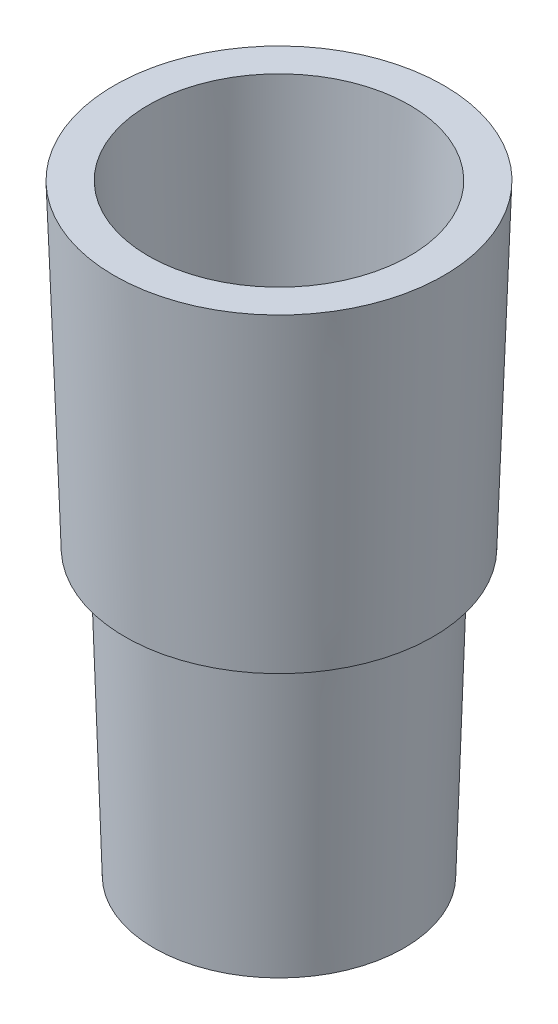
SolidWorks part; units mm, degrees
ref_plane "Front Plane" through (0, 0, 0) normal (0, 0, 1) x (1, 0, 0)
ref_plane "Top Plane" through (0, 0, 0) normal (0, 1, 0) x (1, 0, 0)
ref_plane "Right Plane" through (0, 0, 0) normal (1, 0, 0) x (0, 0, -1)
sketch "Sketch1" plane through (0, 0, 0) normal (0, 0, 1) x (1, 0, 0)
  line L0 (8, 0) -> (8, 28)
  line L2 (10.75, 30.75) -> (11.5, 53)
  line L3 (11.5, 53) -> (14.5, 53)
  line L4 (14.5, 53) -> (13.5562, 25)
  line L5 (13.5562, 25) -> (11.75, 25)
  line L6 (11.75, 25) -> (11, 0)
  line L7 (11, 0) -> (8, 0)
  line L8 (0, 0) -> (0, 41.4703) construction
  line L9 (8, 28) -> (10.75, 30.75)
  point P3 (11, 30.5112)
  dimension "D1" = 3
  dimension "D2" = 22
  dimension "D3" = 23.5
  dimension "D4" = 25
  dimension "D5" = 135
  dimension "D6" = 23
  dimension "D7" = 3
  dimension "D8" = 21.5
  dimension "D9" = 28
  dimension "D10" = 3
revolve "Revolve1" add sketch "Sketch1" angle 360 about L8
